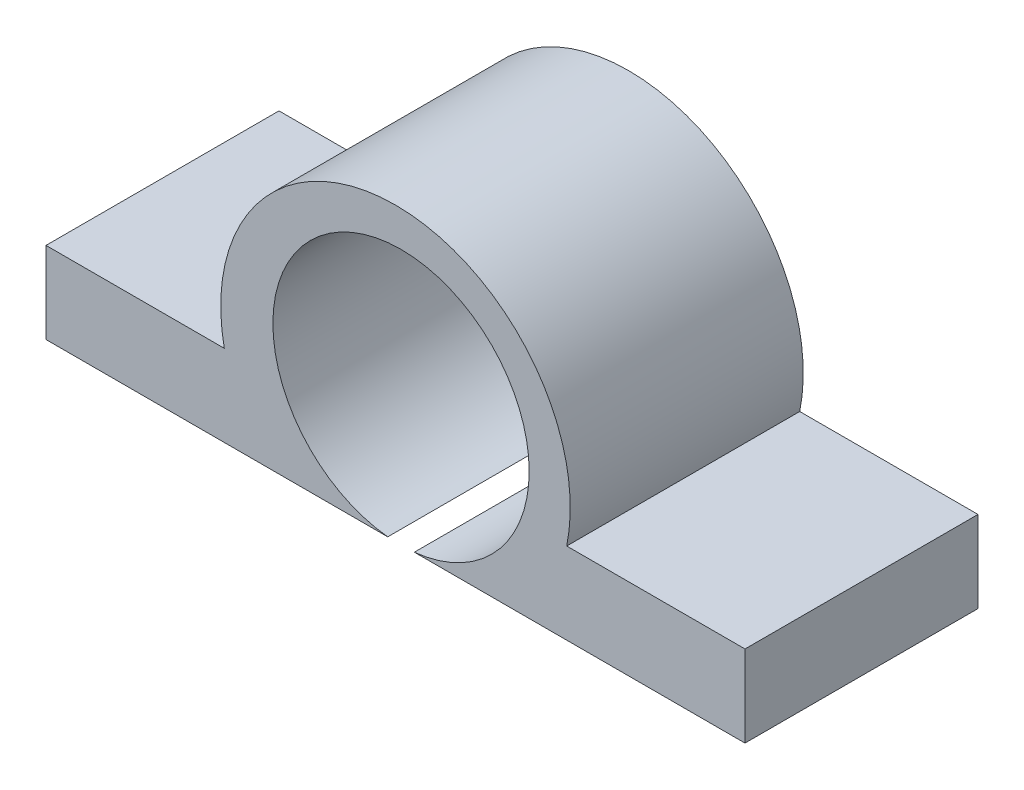
SolidWorks part; units mm, degrees
ref_plane "Front Plane" through (0, 0, 0) normal (0, 0, 1) x (1, 0, 0)
ref_plane "Top Plane" through (0, 0, 0) normal (0, 1, 0) x (1, 0, 0)
ref_plane "Right Plane" through (0, 0, 0) normal (1, 0, 0) x (0, 0, -1)
sketch "Sketch1" plane through (0, 0, 0) normal (0, 0, 1) x (1, 0, 0)
  line L0 (14.6969, 3.5) -> (30, 3.5)
  line L1 (-30, 3.5) -> (-14.6969, 3.5)
  line L2 (-30, 3.5) -> (-30, -3.5)
  line L3 (-30, -3.5) -> (30, -3.5)
  line L4 (30, 3.5) -> (30, -3.5)
  line L5 (-30, 3.5) -> (30, -3.5) construction
  line L6 (-30, -3.5) -> (30, 3.5) construction
  arc A0 (14.6969, 3.5) -> (-14.6969, 3.5) centre (0, 6.5) ccw
  point P0 (0, 0)
  point P9 (0, -3.5)
  dimension "D3" = 30
  dimension "D1" = 60
  dimension "D2" = 7
  dimension "D4" = 10
sketch "Sketch2" plane through (0, 0, 0) normal (0, 0, 1) x (1, 0, 0)
  line L1 (-30, 3.5) -> (-14.6969, 3.5) construction
  circle A0 centre (0, 6.5) radius 15 construction
  point P0 (-14.6969, 3.5)
  point P1 (14.6969, 3.5)
extrude "Boss-Extrude1" add sketch "Sketch1" along normal blind 20
sketch "Sketch3" plane through (0, 0, 20) normal (0, 0, 1) x (1, 0, 0)
  circle A0 centre (0.475, 7.4406) radius 11
  point P0 (0.475, 7.4406)
  dimension "D1" = 22
extrude "Cut-Extrude1" cut sketch "Sketch3" against normal through all
